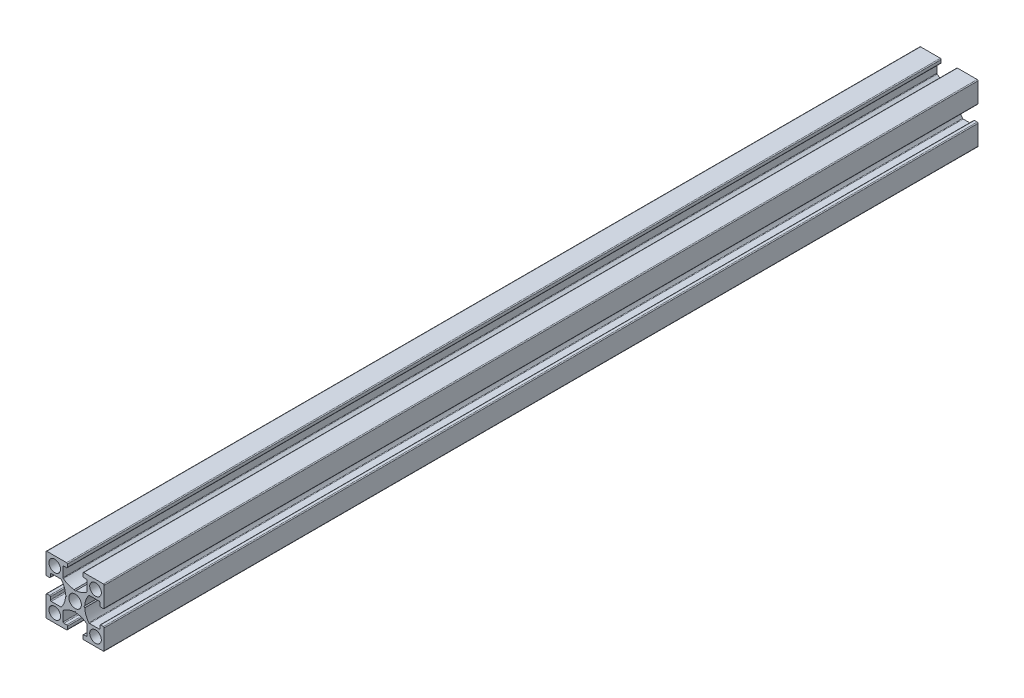
SolidWorks part; units mm, degrees
ref_plane "정면" through (0, 0, 0) normal (0, 0, 1) x (1, 0, 0)
ref_plane "윗면" through (0, 0, 0) normal (0, 1, 0) x (1, 0, 0)
ref_plane "우측면" through (0, 0, 0) normal (1, 0, 0) x (0, 0, -1)
sketch "Model" plane through (0, 0, 0) normal (0, 0, 1) x (1, 0, 0)
  line L0 (2292.4151, 1187.1915) -> (2314.8128, 1187.1915) construction
  line L1 (2307.7639, 1192.1343) -> (2307.7639, 1195.3915)
  line L2 (2307.4639, 1195.6915) -> (2306.5639, 1195.6915)
  line L3 (2306.2639, 1195.9915) -> (2306.2639, 1196.8915)
  line L4 (2306.5639, 1197.1915) -> (2313.3139, 1197.1915)
  line L5 (2313.6139, 1196.8915) -> (2313.6139, 1190.1415)
  line L6 (2313.3139, 1189.8415) -> (2312.4139, 1189.8415)
  line L7 (2312.1139, 1190.1415) -> (2312.1139, 1191.0415)
  line L8 (2311.8139, 1191.3415) -> (2308.5567, 1191.3415)
  line L9 (2306.9212, 1187.4988) -> (2306.6139, 1187.1915)
  line L10 (2306.6139, 1187.1915) -> (2306.9212, 1186.8843)
  line L11 (2308.5567, 1183.0415) -> (2311.8139, 1183.0415)
  line L12 (2312.1139, 1183.3415) -> (2312.1139, 1184.2415)
  line L13 (2312.4139, 1184.5415) -> (2313.3139, 1184.5415)
  line L14 (2313.6139, 1184.2415) -> (2313.6139, 1177.4915)
  line L15 (2313.3139, 1177.1915) -> (2306.5639, 1177.1915)
  line L16 (2306.2639, 1177.4915) -> (2306.2639, 1178.3915)
  line L17 (2306.5639, 1178.6915) -> (2307.4639, 1178.6915)
  line L18 (2307.7639, 1178.9915) -> (2307.7639, 1182.2488)
  line L19 (2303.9212, 1183.8843) -> (2303.6139, 1184.1915)
  line L20 (2303.6139, 1184.1915) -> (2303.3066, 1183.8843)
  line L21 (2299.4639, 1182.2488) -> (2299.4639, 1178.9915)
  line L22 (2299.7639, 1178.6915) -> (2300.6639, 1178.6915)
  line L23 (2300.9639, 1178.3915) -> (2300.9639, 1177.4915)
  line L24 (2300.6639, 1177.1915) -> (2293.9139, 1177.1915)
  line L25 (2293.6139, 1177.4915) -> (2293.6139, 1184.2415)
  line L26 (2293.9139, 1184.5415) -> (2294.8139, 1184.5415)
  line L27 (2295.1139, 1184.2415) -> (2295.1139, 1183.3415)
  line L28 (2295.4139, 1183.0415) -> (2298.6712, 1183.0415)
  line L29 (2300.3066, 1186.8843) -> (2300.6139, 1187.1915)
  line L30 (2300.6139, 1187.1915) -> (2300.3066, 1187.4988)
  line L31 (2298.6712, 1191.3415) -> (2295.4139, 1191.3415)
  line L32 (2295.1139, 1191.0415) -> (2295.1139, 1190.1415)
  line L33 (2294.8139, 1189.8415) -> (2293.9139, 1189.8415)
  line L34 (2293.6139, 1190.1415) -> (2293.6139, 1196.8915)
  line L35 (2293.9139, 1197.1915) -> (2300.6639, 1197.1915)
  line L36 (2300.9639, 1196.8915) -> (2300.9639, 1195.9915)
  line L37 (2300.6639, 1195.6915) -> (2299.7639, 1195.6915)
  line L38 (2299.4639, 1195.3915) -> (2299.4639, 1192.1343)
  line L39 (2303.3066, 1190.4988) -> (2303.6139, 1190.1915)
  line L40 (2303.6139, 1190.1915) -> (2303.9212, 1190.4988)
  line L41 (2294.1139, 1194.1915) -> (2299.1139, 1194.1915) construction
  line L42 (2296.6139, 1196.6915) -> (2296.6139, 1191.6915) construction
  line L43 (2294.1139, 1180.1915) -> (2299.1139, 1180.1915) construction
  line L44 (2296.6139, 1177.6915) -> (2296.6139, 1182.6915) construction
  line L45 (2303.6139, 1198.3904) -> (2303.6139, 1175.9927) construction
  line L46 (2313.1139, 1194.1915) -> (2308.1139, 1194.1915) construction
  line L47 (2310.6139, 1196.6915) -> (2310.6139, 1191.6915) construction
  line L48 (2310.6139, 1177.6915) -> (2310.6139, 1182.6915) construction
  line L49 (2313.1139, 1180.1915) -> (2308.1139, 1180.1915) construction
  circle A0 centre (2303.6139, 1187.1915) radius 2.15
  circle A1 centre (2296.6139, 1194.1915) radius 2
  circle A2 centre (2296.6139, 1180.1915) radius 2
  circle A3 centre (2310.6139, 1194.1915) radius 2
  circle A4 centre (2310.6139, 1180.1915) radius 2
  arc A5 (2307.7639, 1195.3915) -> (2307.4639, 1195.6915) centre (2307.4639, 1195.3915) ccw
  arc A6 (2306.2639, 1195.9915) -> (2306.5639, 1195.6915) centre (2306.5639, 1195.9915) ccw
  arc A7 (2306.5639, 1197.1915) -> (2306.2639, 1196.8915) centre (2306.5639, 1196.8915) ccw
  arc A8 (2313.6139, 1196.8915) -> (2313.3139, 1197.1915) centre (2313.3139, 1196.8915) ccw
  arc A9 (2313.3139, 1189.8415) -> (2313.6139, 1190.1415) centre (2313.3139, 1190.1415) ccw
  arc A10 (2312.1139, 1190.1415) -> (2312.4139, 1189.8415) centre (2312.4139, 1190.1415) ccw
  arc A11 (2312.1139, 1191.0415) -> (2311.8139, 1191.3415) centre (2311.8139, 1191.0415) ccw
  arc A12 (2308.5567, 1191.3415) -> (2308.3217, 1191.2281) centre (2308.5567, 1191.0415) ccw
  arc A13 (2308.3217, 1191.2281) -> (2306.9212, 1187.4988) centre (2313.4048, 1187.1915) ccw
  arc A14 (2306.9212, 1186.8843) -> (2308.3217, 1183.155) centre (2313.4048, 1187.1915) ccw
  arc A15 (2308.3217, 1183.155) -> (2308.5567, 1183.0415) centre (2308.5567, 1183.3415) ccw
  arc A16 (2311.8139, 1183.0415) -> (2312.1139, 1183.3415) centre (2311.8139, 1183.3415) ccw
  arc A17 (2312.4139, 1184.5415) -> (2312.1139, 1184.2415) centre (2312.4139, 1184.2415) ccw
  arc A18 (2313.6139, 1184.2415) -> (2313.3139, 1184.5415) centre (2313.3139, 1184.2415) ccw
  arc A19 (2313.3139, 1177.1915) -> (2313.6139, 1177.4915) centre (2313.3139, 1177.4915) ccw
  arc A20 (2306.2639, 1177.4915) -> (2306.5639, 1177.1915) centre (2306.5639, 1177.4915) ccw
  arc A21 (2306.5639, 1178.6915) -> (2306.2639, 1178.3915) centre (2306.5639, 1178.3915) ccw
  arc A22 (2307.4639, 1178.6915) -> (2307.7639, 1178.9915) centre (2307.4639, 1178.9915) ccw
  arc A23 (2307.7639, 1182.2488) -> (2307.6505, 1182.4837) centre (2307.4639, 1182.2488) ccw
  arc A24 (2307.6505, 1182.4837) -> (2303.9212, 1183.8843) centre (2303.6139, 1177.4007) ccw
  arc A25 (2303.3066, 1183.8843) -> (2299.5774, 1182.4837) centre (2303.6139, 1177.4007) ccw
  arc A26 (2299.5774, 1182.4837) -> (2299.4639, 1182.2488) centre (2299.7639, 1182.2488) ccw
  arc A27 (2299.4639, 1178.9915) -> (2299.7639, 1178.6915) centre (2299.7639, 1178.9915) ccw
  arc A28 (2300.9639, 1178.3915) -> (2300.6639, 1178.6915) centre (2300.6639, 1178.3915) ccw
  arc A29 (2300.6639, 1177.1915) -> (2300.9639, 1177.4915) centre (2300.6639, 1177.4915) ccw
  arc A30 (2293.6139, 1177.4915) -> (2293.9139, 1177.1915) centre (2293.9139, 1177.4915) ccw
  arc A31 (2293.9139, 1184.5415) -> (2293.6139, 1184.2415) centre (2293.9139, 1184.2415) ccw
  arc A32 (2295.1139, 1184.2415) -> (2294.8139, 1184.5415) centre (2294.8139, 1184.2415) ccw
  arc A33 (2295.1139, 1183.3415) -> (2295.4139, 1183.0415) centre (2295.4139, 1183.3415) ccw
  arc A34 (2298.6712, 1183.0415) -> (2298.9061, 1183.155) centre (2298.6712, 1183.3415) ccw
  arc A35 (2298.9061, 1183.155) -> (2300.3066, 1186.8843) centre (2293.8231, 1187.1915) ccw
  arc A36 (2300.3066, 1187.4988) -> (2298.9061, 1191.2281) centre (2293.8231, 1187.1915) ccw
  arc A37 (2298.9061, 1191.2281) -> (2298.6712, 1191.3415) centre (2298.6712, 1191.0415) ccw
  arc A38 (2295.4139, 1191.3415) -> (2295.1139, 1191.0415) centre (2295.4139, 1191.0415) ccw
  arc A39 (2294.8139, 1189.8415) -> (2295.1139, 1190.1415) centre (2294.8139, 1190.1415) ccw
  arc A40 (2293.6139, 1190.1415) -> (2293.9139, 1189.8415) centre (2293.9139, 1190.1415) ccw
  arc A41 (2293.9139, 1197.1915) -> (2293.6139, 1196.8915) centre (2293.9139, 1196.8915) ccw
  arc A42 (2300.9639, 1196.8915) -> (2300.6639, 1197.1915) centre (2300.6639, 1196.8915) ccw
  arc A43 (2300.6639, 1195.6915) -> (2300.9639, 1195.9915) centre (2300.6639, 1195.9915) ccw
  arc A44 (2299.7639, 1195.6915) -> (2299.4639, 1195.3915) centre (2299.7639, 1195.3915) ccw
  arc A45 (2299.4639, 1192.1343) -> (2299.5774, 1191.8994) centre (2299.7639, 1192.1343) ccw
  arc A46 (2299.5774, 1191.8994) -> (2303.3066, 1190.4988) centre (2303.6139, 1196.9824) ccw
  arc A47 (2303.9212, 1190.4988) -> (2307.6505, 1191.8994) centre (2303.6139, 1196.9824) ccw
  arc A48 (2307.6505, 1191.8994) -> (2307.7639, 1192.1343) centre (2307.4639, 1192.1343) ccw
extrude "보스-돌출1" add sketch "Model" along normal blind 300
